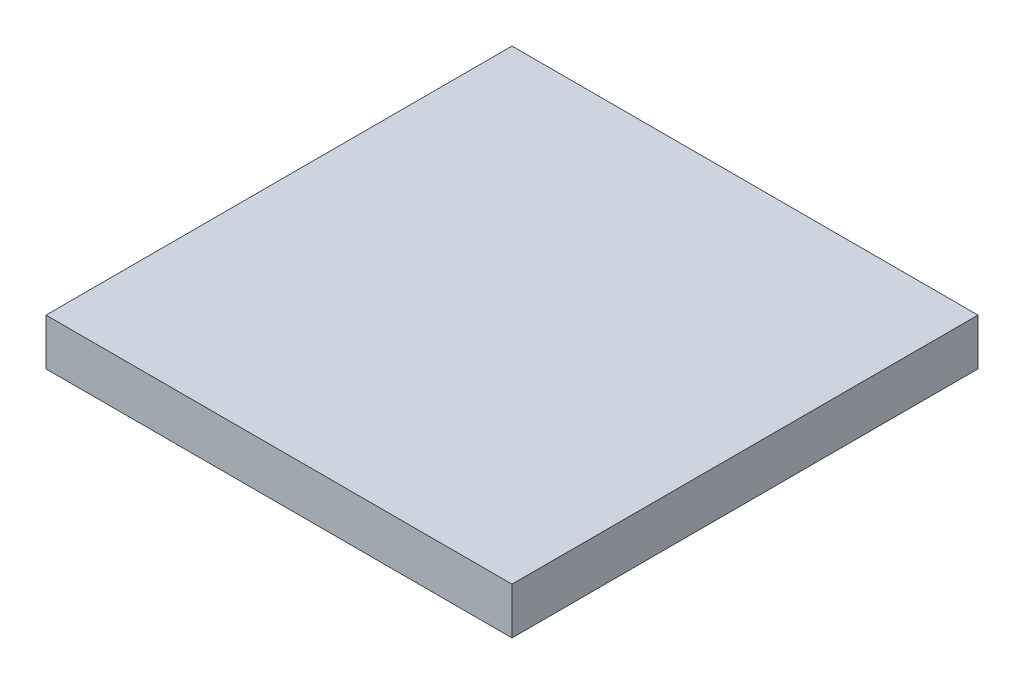
SolidWorks part; units mm, degrees
ref_plane "Front Plane" through (0, 0, 0) normal (0, 0, 1) x (1, 0, 0)
ref_plane "Top Plane" through (0, 0, 0) normal (0, 1, 0) x (1, 0, 0)
ref_plane "Right Plane" through (0, 0, 0) normal (1, 0, 0) x (0, 0, -1)
sketch "Sketch3" plane through (0, 0, 0) normal (0, 1, 0) x (1, 0, 0)
  line L1 (-250, 250) -> (250, 250)
  line L2 (-250, 250) -> (-250, -250)
  line L3 (-250, -250) -> (250, -250)
  line L4 (250, 250) -> (250, -250)
  line L5 (-250, 250) -> (250, -250) construction
  line L6 (-250, -250) -> (250, 250) construction
  point P0 (0, 0)
  dimension "D1" = 500
  dimension "D2" = 500
extrude "Boss-Extrude1" add sketch "Sketch3" along normal blind 50
